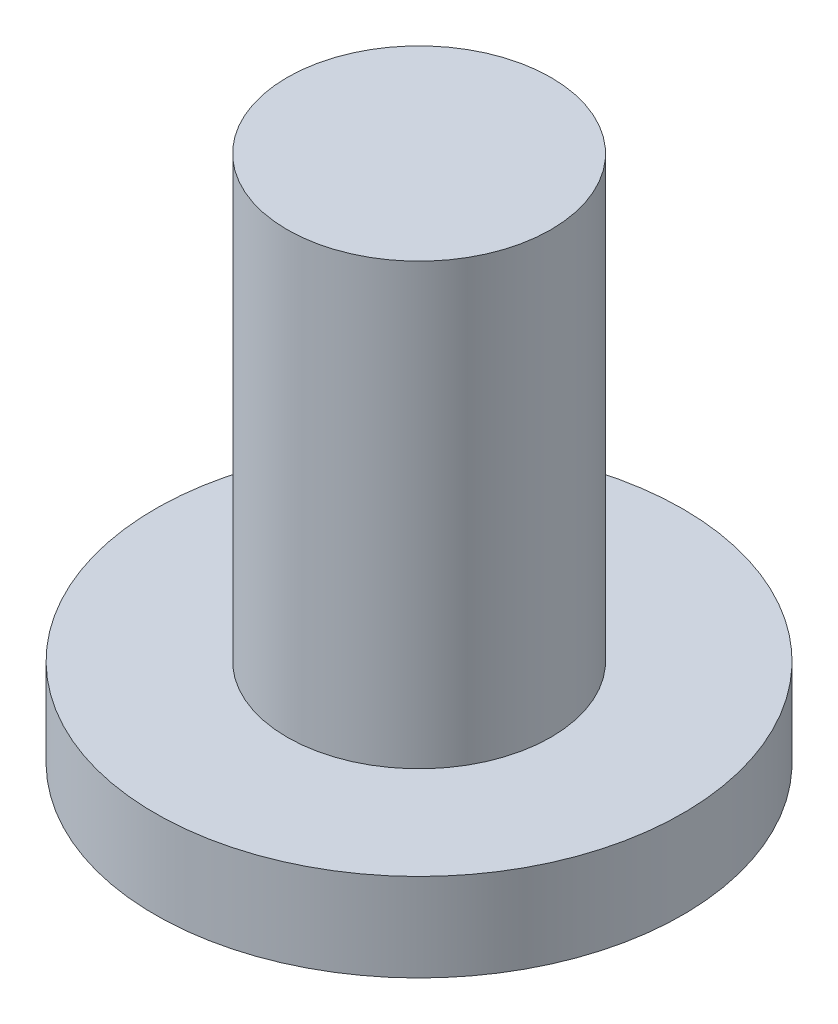
SolidWorks part; units mm, degrees
ref_plane "Front Plane" through (0, 0, 0) normal (0, 0, 1) x (1, 0, 0)
ref_plane "Top Plane" through (0, 0, 0) normal (0, 1, 0) x (1, 0, 0)
ref_plane "Right Plane" through (0, 0, 0) normal (1, 0, 0) x (0, 0, -1)
sketch "Sketch1" plane through (0, 0, 0) normal (0, 1, 0) x (1, 0, 0)
  circle A1 centre (0, 0) radius 3
  dimension "D1" = 6
extrude "Boss-Extrude1" add sketch "Sketch1" along normal mid plane 10
sketch "Sketch2" plane through (0, -5, 0) normal (0, -1, 0) x (1, 0, 0)
  circle A0 centre (0, 0) radius 6
  dimension "D1" = 12
extrude "Boss-Extrude2" add sketch "Sketch2" along normal blind 2
